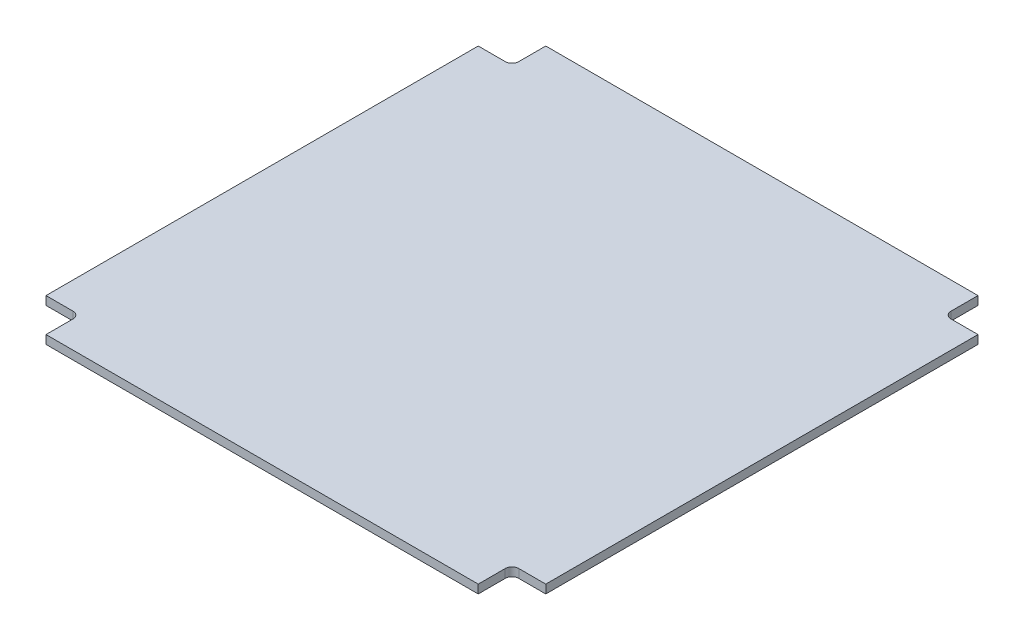
SolidWorks part; units mm, degrees
material "Acrylic (Medium-high impact)"
ref_plane "Front Plane" through (0, 0, 0) normal (0, 0, 1) x (1, 0, 0)
ref_plane "Top Plane" through (0, 0, 0) normal (0, 1, 0) x (1, 0, 0)
ref_plane "Right Plane" through (0, 0, 0) normal (1, 0, 0) x (0, 0, -1)
sketch "Sketch1" plane through (0, 0, 0) normal (0, 1, 0) x (1, 0, 0)
  line L1 (185, 185) -> (-185, 185)
  line L2 (-185, 185) -> (-185, -185)
  line L3 (-185, -185) -> (185, -185)
  line L4 (185, -185) -> (185, 185)
  circle A0 centre (0, 0) radius 185 construction
  dimension "D1" = 370
extrude "Boss-Extrude1" add sketch "Sketch1" along normal blind 6.35
sketch "Sketch2" plane through (0, 0, 0) normal (0, 1, 0) x (1, 0, 0)
  line L0 (-185, 185) -> (-185, 160)
  line L1 (-185, -185) -> (-160, -185)
  line L2 (-160, -185) -> (-160, -165)
  line L3 (-165, -160) -> (-185, -160)
  line L4 (-185, -160) -> (-185, -185)
  line L5 (-185, 160) -> (-165, 160)
  line L6 (-160, 165) -> (-160, 185)
  line L7 (-160, 185) -> (-185, 185)
  line L8 (185, 185) -> (160, 185)
  line L9 (160, 185) -> (160, 165)
  line L10 (165, 160) -> (185, 160)
  line L11 (185, 160) -> (185, 185)
  line L12 (185, -185) -> (185, -160)
  line L13 (185, -160) -> (165, -160)
  line L14 (160, -165) -> (160, -185)
  line L15 (160, -185) -> (185, -185)
  circle A0 centre (-172.5, -172.5) radius 12.5 construction
  arc A1 (-160, -165) -> (-165, -160) centre (-165, -165) ccw
  arc A2 (-165, 160) -> (-160, 165) centre (-165, 165) ccw
  circle A3 centre (-172.5, 172.5) radius 12.5 construction
  arc A4 (160, 165) -> (165, 160) centre (165, 165) ccw
  circle A5 centre (172.5, 172.5) radius 12.5 construction
  arc A6 (165, -160) -> (160, -165) centre (165, -165) ccw
  circle A7 centre (172.5, -172.5) radius 12.5 construction
  point P36 (0, 0)
  point P37 (0, 0)
  dimension "D2" = 5
  dimension "D1" = 25
  dimension "D3" = 4
extrude "Cut-Extrude2" cut sketch "Sketch2" along normal up to next and the other way through all
